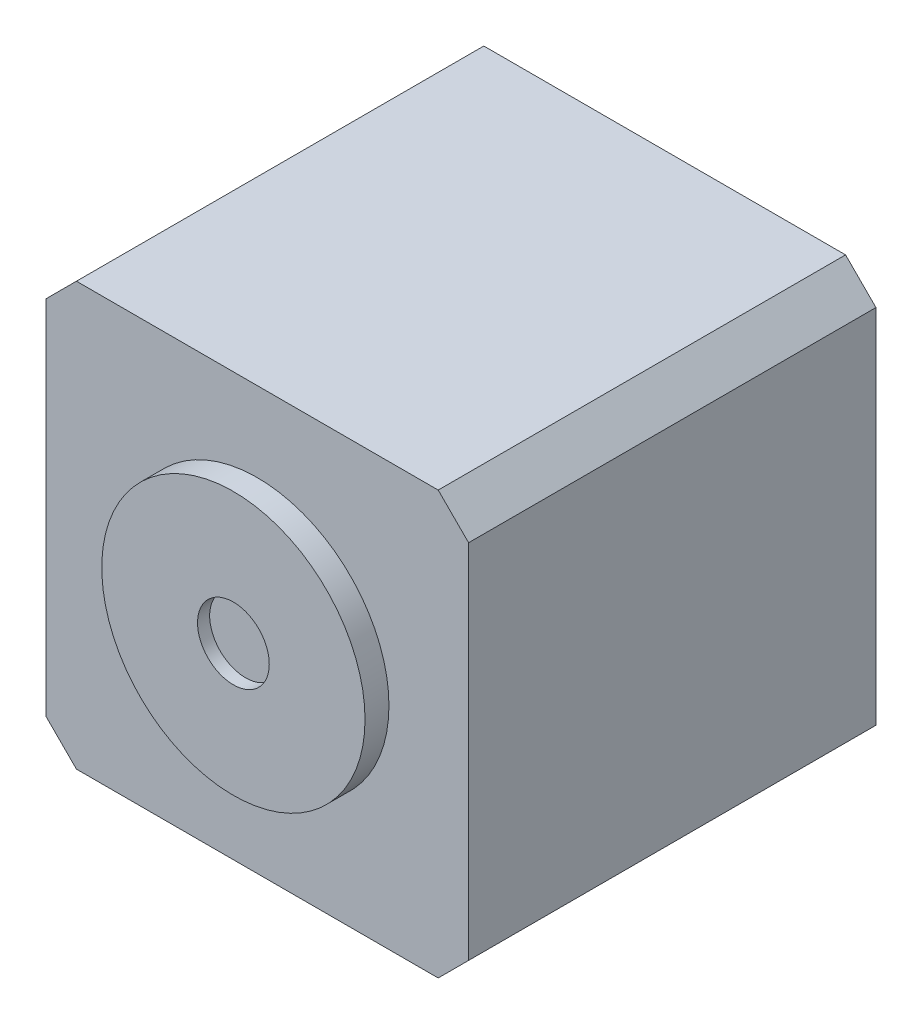
SolidWorks part; units mm, degrees
ref_plane "Front Plane" through (0, 0, 0) normal (0, 0, 1) x (1, 0, 0)
ref_plane "Top Plane" through (0, 0, 0) normal (0, 1, 0) x (1, 0, 0)
ref_plane "Right Plane" through (0, 0, 0) normal (1, 0, 0) x (0, 0, -1)
sketch "Sketch1" plane through (0, 0, 0) normal (0, 0, 1) x (1, 0, 0)
  line L1 (17.653, -17.653) -> (-17.653, -17.653)
  line L2 (17.653, -17.653) -> (17.653, 17.653)
  line L3 (17.653, 17.653) -> (-17.653, 17.653)
  line L4 (-17.653, -17.653) -> (-17.653, 17.653)
  line L5 (17.653, -17.653) -> (-17.653, 17.653) construction
  line L6 (17.653, 17.653) -> (-17.653, -17.653) construction
  point P0 (0, 0)
  dimension "D1" = 35.306
extrude "Boss-Extrude1" add sketch "Sketch1" along normal blind 34.036
sketch "Sketch2" plane through (0, 0, 34.036) normal (0, 0, 1) x (1, 0, 0)
  circle A0 centre (0, 0) radius 10.9982
  dimension "D1" = 21.9964
extrude "Boss-Extrude2" add sketch "Sketch2" along normal blind 1.999
sketch "Sketch3" plane through (0, 0, 36.035) normal (0, 0, 1) x (1, 0, 0)
  circle A0 centre (0, 0) radius 2.9972
  dimension "D1" = 5.9944
extrude "Cut-Extrude1" cut sketch "Sketch3" against normal blind 1.016
chamfer "Chamfer1" distance 2.54 angle 45 4 edges at (-17.653, 17.653, 17.018) (17.653, 17.653, 17.018) (17.653, -17.653, 17.018) (-17.653, -17.653, 17.018)
